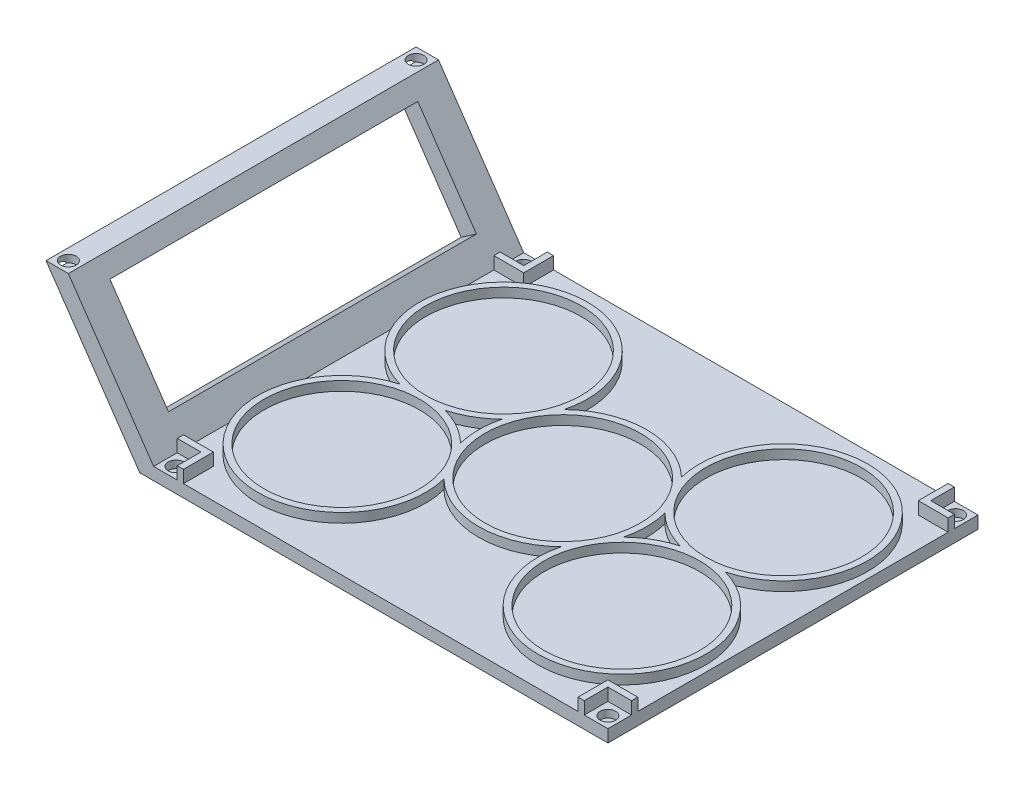
SolidWorks part; units mm, degrees
ref_plane "Front Plane" through (0, 0, 0) normal (0, 0, 1) x (1, 0, 0)
ref_plane "Top Plane" through (0, 0, 0) normal (0, 1, 0) x (1, 0, 0)
ref_plane "Right Plane" through (0, 0, 0) normal (1, 0, 0) x (0, 0, -1)
sketch "Sketch1" plane through (0, 0, 0) normal (0, 1, 0) x (1, 0, 0)
  line L1 (-187.7209, 14.7284) -> (-114.6876, 14.7284)
  line L2 (-187.7209, 14.7284) -> (-187.7209, -44.7716)
  line L3 (-187.7209, -44.7716) -> (-114.6876, -44.7716)
  line L4 (-114.6876, 14.7284) -> (-114.6876, -44.7716)
extrude "Boss-Extrude1" add sketch "Sketch1" along normal blind 2
sketch "Sketch2" plane through (0, 2, 0) normal (0, 1, 0) x (1, 0, 0)
  line L0 (-114.6876, -15.0216) -> (-114.6876, -28.0216)
  line L1 (-114.6876, -44.7716) -> (-114.6876, 14.7284) construction
  line L2 (-114.6876, -28.0216) -> (-129.1876, -28.0216)
  line L3 (-114.6876, -15.0216) -> (-114.6876, -2.0216)
  line L4 (-114.6876, -2.0216) -> (-129.1876, -2.0216)
  line L5 (-129.1876, -2.0216) -> (-151.7042, -15.0216)
  line L6 (-151.7042, -15.0216) -> (-174.2209, -2.0216)
  line L7 (-151.7042, -15.0216) -> (-174.2209, -28.0216)
  circle A0 centre (-129.1876, -28.0216) radius 13.5
  circle A1 centre (-129.1876, -2.0216) radius 13.5
  circle A2 centre (-151.7042, -15.0216) radius 13.5
  circle A3 centre (-174.2209, -2.0216) radius 13.5
  circle A4 centre (-174.2209, -28.0216) radius 13.5
  circle A5 centre (-174.2209, -28.0216) radius 12.5
  circle A6 centre (-174.2209, -2.0216) radius 12.5
  circle A7 centre (-151.7042, -15.0216) radius 12.5
  circle A8 centre (-129.1876, -2.0216) radius 12.5
  circle A9 centre (-129.1876, -28.0216) radius 12.5
extrude "Boss-Extrude2" add sketch "Sketch2" along normal blind 1.5 contours A6 A2 A3 A4 | A5 A3 A4 A2 | A3 A4 | A6 A4 A3 A2 | A5 A2 A4 A3 | L6 A3 A2 | A2 A3 L6 | A7 A3 A2 A4 | L7 A4 A2 | A2 A4 L7 | A7 A4 A2 A0 | A7 A1 A2 A3 | L5 A2 A1 | A1 A2 L5 | A7 A0 A2 A1 | A0 A2 | A9 A2 A0 L2 | A9 L2 A0 A1 | A9 A1 A0 A2 | A0 A1 | A8 A2 A1 A0 | A8 L4 A1 A2 | A8 A0 A1 L4
sketch "Sketch3" plane through (0, 2, 0) normal (0, 1, 0) x (1, 0, 0)
  line L1 (-114.6876, -44.7716) -> (-118.2876, -44.7716)
  line L2 (-114.6876, -44.7716) -> (-114.6876, -41.1716)
  line L3 (-114.6876, -41.1716) -> (-118.2876, -41.1716)
  line L5 (-114.6876, 14.7284) -> (-118.2876, 14.7284)
  line L6 (-114.6876, 14.7284) -> (-114.6876, 11.1284)
  line L8 (-118.2876, 14.7284) -> (-118.2876, 11.1284)
  line L9 (-187.7209, 14.7284) -> (-184.1209, 14.7284)
  line L10 (-187.7209, 14.7284) -> (-187.7209, 11.1284)
  line L12 (-184.1209, 14.7284) -> (-184.1209, 11.1284)
  line L13 (-187.7209, -44.7716) -> (-184.1209, -44.7716)
  line L14 (-187.7209, -44.7716) -> (-187.7209, -41.1716)
  line L15 (-187.7209, -41.1716) -> (-184.1209, -41.1716)
  circle A0 centre (-185.9209, -42.9716) radius 1.25
  circle A1 centre (-116.4876, -42.9716) radius 1.25
  circle A2 centre (-116.4876, 12.9284) radius 1.25
  circle A3 centre (-185.9209, 12.9284) radius 1.25
extrude "Cut-Extrude1" cut sketch "Sketch3" against normal blind 1.2 contours A3 | A0 | A1 | A2
sketch "Sketch4" plane through (0, 0, 44.7716) normal (0, 0, 1) x (1, 0, 0)
  line L2 (-201.4209, 22) -> (-187.7209, 2)
  line L3 (-201.4209, 22) -> (-205.0209, 22)
  line L4 (-187.7209, 2) -> (-187.7209, 0)
  line L6 (-191.3209, 2) -> (-205.0209, 22)
  line L7 (-191.3209, 2) -> (-189.9509, 0)
  line L8 (-189.9509, 0) -> (-187.7209, 0)
extrude "Boss-Extrude3" add sketch "Sketch4" against normal blind 59.5
sketch "Sketch5" plane through (0, 22, 0) normal (0, 1, 0) x (1, 0, 0)
  line L0 (-201.4209, 14.7284) -> (-201.4209, -44.7716) construction
  line L1 (-205.0209, -44.7716) -> (-201.4209, -44.7716)
  line L2 (-205.0209, -44.7716) -> (-205.0209, -41.1716)
  line L4 (-201.4209, -44.7716) -> (-201.4209, -41.1716)
  line L6 (-205.0209, 14.7284) -> (-201.4209, 14.7284)
  line L7 (-205.0209, 14.7284) -> (-205.0209, 11.1284)
  line L9 (-201.4209, 14.7284) -> (-201.4209, 11.1284)
  circle A0 centre (-203.2209, 12.9284) radius 1.25
  circle A1 centre (-203.2209, -42.9716) radius 1.25
extrude "Cut-Extrude2" cut sketch "Sketch5" against normal blind 1.2 contours A0 | A1
sketch "Sketch7" plane through (-129.2865, -88.5612, 0) normal (-0.825, -0.5651, 0) x (0, 0, 1)
  line L2 (-14.7284, 134.013) -> (-9.7284, 134.013)
  line L3 (-14.7284, 134.013) -> (-14.7284, 129.013)
  line L4 (-14.7284, 129.013) -> (-9.7284, 129.013)
  line L5 (-9.7284, 134.013) -> (-9.7284, 129.013)
  line L6 (44.7716, 107.3465) -> (39.7716, 107.3465)
  line L7 (44.7716, 107.3465) -> (44.7716, 112.3465)
  line L8 (44.7716, 112.3465) -> (39.7716, 112.3465)
  line L9 (39.7716, 107.3465) -> (39.7716, 112.3465)
  line L10 (-9.7284, 129.013) -> (39.7716, 129.013)
  line L11 (-9.7284, 129.013) -> (-9.7284, 112.3465)
  line L12 (-9.7284, 112.3465) -> (39.7716, 112.3465)
  line L13 (39.7716, 129.013) -> (39.7716, 112.3465)
extrude "Cut-Extrude4" cut sketch "Sketch7" against normal blind 3.6 contours L13 L10 L11 L12
sketch "Sketch8" plane through (0, 2, 0) normal (0, 1, 0) x (1, 0, 0)
  line L1 (-187.7209, -44.7716) -> (-183.9209, -44.7716)
  line L2 (-187.7209, -44.7716) -> (-187.7209, -40.9716)
  line L3 (-187.7209, -40.9716) -> (-183.9209, -40.9716)
  line L4 (-183.9209, -44.7716) -> (-183.9209, -40.9716)
  line L5 (-187.7209, -44.7716) -> (-182.9209, -44.7716)
  line L6 (-187.7209, -44.7716) -> (-187.7209, -39.9716)
  line L7 (-187.7209, -39.9716) -> (-182.9209, -39.9716)
  line L8 (-182.9209, -44.7716) -> (-182.9209, -39.9716)
  line L9 (-114.6876, -44.7716) -> (-119.4876, -44.7716)
  line L10 (-114.6876, -44.7716) -> (-114.6876, -39.9716)
  line L11 (-114.6876, -39.9716) -> (-119.4876, -39.9716)
  line L12 (-119.4876, -44.7716) -> (-119.4876, -39.9716)
  line L13 (-114.6876, -44.7716) -> (-118.4876, -44.7716)
  line L14 (-114.6876, -44.7716) -> (-114.6876, -40.9716)
  line L15 (-114.6876, -40.9716) -> (-118.4876, -40.9716)
  line L16 (-118.4876, -44.7716) -> (-118.4876, -40.9716)
  line L17 (-187.7209, 14.7284) -> (-183.9209, 14.7284)
  line L18 (-187.7209, 14.7284) -> (-187.7209, 10.9284)
  line L19 (-187.7209, 10.9284) -> (-183.9209, 10.9284)
  line L20 (-183.9209, 14.7284) -> (-183.9209, 10.9284)
  line L21 (-187.7209, 14.7284) -> (-182.9209, 14.7284)
  line L22 (-187.7209, 14.7284) -> (-187.7209, 9.9284)
  line L23 (-187.7209, 9.9284) -> (-182.9209, 9.9284)
  line L24 (-182.9209, 14.7284) -> (-182.9209, 9.9284)
  line L25 (-114.6876, 14.7284) -> (-118.4876, 14.7284)
  line L26 (-114.6876, 14.7284) -> (-114.6876, 10.9284)
  line L27 (-114.6876, 10.9284) -> (-118.4876, 10.9284)
  line L28 (-118.4876, 14.7284) -> (-118.4876, 10.9284)
  line L29 (-114.6876, 14.7284) -> (-119.4876, 14.7284)
  line L30 (-114.6876, 14.7284) -> (-114.6876, 9.9284)
  line L31 (-114.6876, 9.9284) -> (-119.4876, 9.9284)
  line L32 (-119.4876, 14.7284) -> (-119.4876, 9.9284)
  line M34 (-187.7209, -28.0216) -> (-187.7209, -44.7716)
  line M35 (-187.7209, -44.7716) -> (-114.6876, -44.7716)
  line M36 (-114.6876, -44.7716) -> (-114.6876, 14.7284)
  line M37 (-114.6876, 14.7284) -> (-187.7209, 14.7284)
  line M38 (-187.7209, 14.7284) -> (-187.7209, -2.0216)
extrude "Boss-Extrude4" add sketch "Sketch8" along normal blind 2 contours L24 L20 L19 L23 M37 M38 | L8 L7 L3 L4 M35 M34 | L16 L15 L10 L11 L12 M35 | L32 L31 L27 L28 M37 M36
